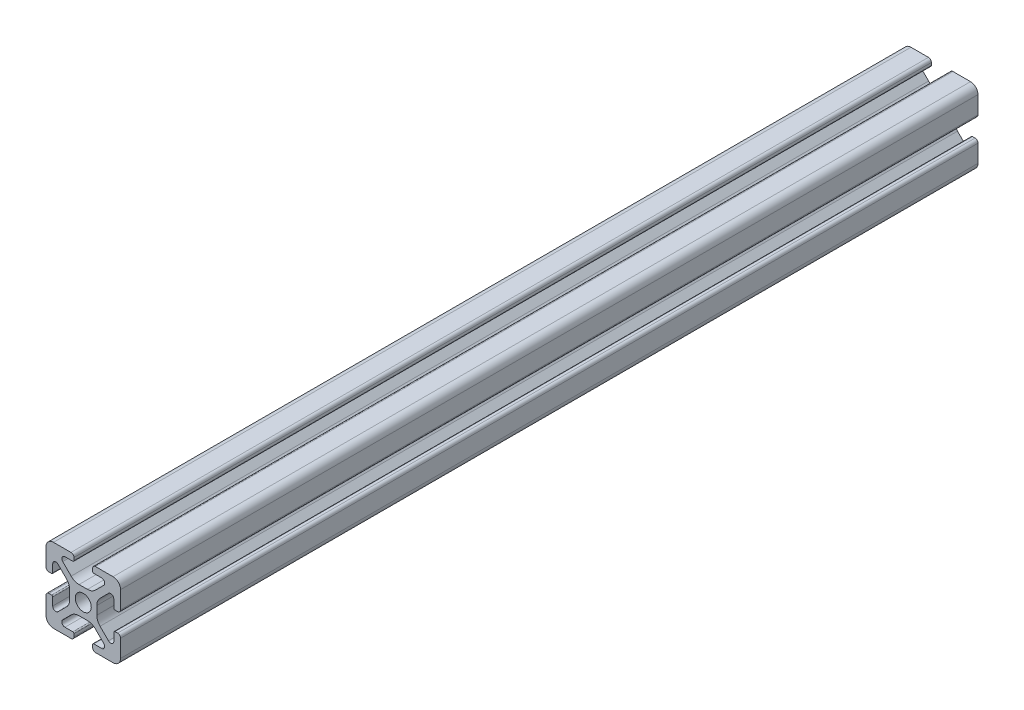
SolidWorks part; units mm, degrees
ref_plane "Front Plane" through (0, 0, 0) normal (0, 0, 1) x (1, 0, 0)
ref_plane "Top Plane" through (0, 0, 0) normal (0, 1, 0) x (1, 0, 0)
ref_plane "Right Plane" through (0, 0, 0) normal (1, 0, 0) x (0, 0, -1)
sketch "Sketch1" plane through (0, 0, 0) normal (0, 0, 1) x (1, 0, 0)
  line L2 (-9.9949, 7.9883) -> (-9.9949, 3.2893)
  line L3 (-7.9883, 9.9949) -> (-3.2893, 9.9949)
  line L4 (-2.5019, 9.2075) -> (-2.5019, 8.4963)
  line L5 (-2.8067, 8.1915) -> (-4.9149, 8.1915)
  line L6 (-5.5076, 6.7606) -> (-3.2528, 4.5058)
  line L7 (-6.7606, 5.5076) -> (-4.5058, 3.2528)
  line L8 (-8.1915, 4.9149) -> (-8.1915, 2.8067)
  line L9 (-8.4963, 2.5019) -> (-9.2075, 2.5019)
  line L11 (-1.1334, 3.6279) -> (1.1334, 3.6279)
  line L12 (-3.6279, 1.1334) -> (-3.6279, -1.1334)
  line L13 (8.4963, 2.5019) -> (9.2075, 2.5019)
  line L14 (8.1915, 4.9149) -> (8.1915, 2.8067)
  line L15 (9.9949, 7.9883) -> (9.9949, 3.2893)
  line L16 (7.9883, 9.9949) -> (3.2893, 9.9949)
  line L17 (2.5019, 9.2075) -> (2.5019, 8.4963)
  line L18 (2.8067, 8.1915) -> (4.9149, 8.1915)
  line L19 (3.6279, 1.1334) -> (3.6279, -1.1334)
  line L20 (5.5076, 6.7606) -> (3.2528, 4.5058)
  line L21 (6.7606, 5.5076) -> (4.5058, 3.2528)
  line L22 (-8.4963, -2.5019) -> (-9.2075, -2.5019)
  line L23 (-8.1915, -4.9149) -> (-8.1915, -2.8067)
  line L24 (-6.7606, -5.5076) -> (-4.5058, -3.2528)
  line L25 (-5.5076, -6.7606) -> (-3.2528, -4.5058)
  line L26 (-2.8067, -8.1915) -> (-4.9149, -8.1915)
  line L27 (-2.5019, -9.2075) -> (-2.5019, -8.4963)
  line L28 (-7.9883, -9.9949) -> (-3.2893, -9.9949)
  line L29 (-9.9949, -7.9883) -> (-9.9949, -3.2893)
  line L30 (9.9949, -7.9883) -> (9.9949, -3.2893)
  line L31 (7.9883, -9.9949) -> (3.2893, -9.9949)
  line L32 (2.5019, -9.2075) -> (2.5019, -8.4963)
  line L33 (2.8067, -8.1915) -> (4.9149, -8.1915)
  line L34 (5.5076, -6.7606) -> (3.2528, -4.5058)
  line L35 (6.7606, -5.5076) -> (4.5058, -3.2528)
  line L36 (8.1915, -4.9149) -> (8.1915, -2.8067)
  line L37 (8.4963, -2.5019) -> (9.2075, -2.5019)
  line L38 (-1.1334, -3.6279) -> (1.1334, -3.6279)
  circle A0 centre (0, 0) radius 2.1463
  arc A1 (-9.9949, 7.9883) -> (-7.9883, 9.9949) centre (-7.9883, 7.9883) cw
  arc A2 (-6.7606, 5.5076) -> (-8.1915, 4.9149) centre (-7.3533, 4.9149) ccw
  arc A3 (-4.9149, 8.1915) -> (-5.5076, 6.7606) centre (-4.9149, 7.3533) ccw
  arc A4 (-3.2893, 9.9949) -> (-2.5019, 9.2075) centre (-3.2893, 9.2075) cw
  arc A5 (-9.9949, 3.2893) -> (-9.2075, 2.5019) centre (-9.2075, 3.2893) ccw
  arc A6 (-8.1915, 2.8067) -> (-8.4963, 2.5019) centre (-8.4963, 2.8067) cw
  arc A7 (-2.5019, 8.4963) -> (-2.8067, 8.1915) centre (-2.8067, 8.4963) cw
  arc A8 (-1.1334, 3.6279) -> (-3.2528, 4.5058) centre (-1.1334, 6.6251) cw
  arc A9 (-3.6279, 1.1334) -> (-4.5058, 3.2528) centre (-6.6251, 1.1334) ccw
  arc A10 (8.1915, 2.8067) -> (8.4963, 2.5019) centre (8.4963, 2.8067) ccw
  arc A11 (9.9949, 3.2893) -> (9.2075, 2.5019) centre (9.2075, 3.2893) cw
  arc A12 (9.9949, 7.9883) -> (7.9883, 9.9949) centre (7.9883, 7.9883) ccw
  arc A13 (3.2893, 9.9949) -> (2.5019, 9.2075) centre (3.2893, 9.2075) ccw
  arc A14 (2.5019, 8.4963) -> (2.8067, 8.1915) centre (2.8067, 8.4963) ccw
  arc A15 (1.1334, 3.6279) -> (3.2528, 4.5058) centre (1.1334, 6.6251) ccw
  arc A16 (3.6279, 1.1334) -> (4.5058, 3.2528) centre (6.6251, 1.1334) cw
  arc A17 (6.7606, 5.5076) -> (8.1915, 4.9149) centre (7.3533, 4.9149) cw
  arc A18 (4.9149, 8.1915) -> (5.5076, 6.7606) centre (4.9149, 7.3533) cw
  arc A19 (-3.6279, -1.1334) -> (-4.5058, -3.2528) centre (-6.6251, -1.1334) cw
  arc A20 (-1.1334, -3.6279) -> (-3.2528, -4.5058) centre (-1.1334, -6.6251) ccw
  arc A21 (-2.5019, -8.4963) -> (-2.8067, -8.1915) centre (-2.8067, -8.4963) ccw
  arc A22 (-8.1915, -2.8067) -> (-8.4963, -2.5019) centre (-8.4963, -2.8067) ccw
  arc A23 (-9.9949, -3.2893) -> (-9.2075, -2.5019) centre (-9.2075, -3.2893) cw
  arc A24 (-3.2893, -9.9949) -> (-2.5019, -9.2075) centre (-3.2893, -9.2075) ccw
  arc A25 (-4.9149, -8.1915) -> (-5.5076, -6.7606) centre (-4.9149, -7.3533) cw
  arc A26 (-6.7606, -5.5076) -> (-8.1915, -4.9149) centre (-7.3533, -4.9149) cw
  arc A27 (-9.9949, -7.9883) -> (-7.9883, -9.9949) centre (-7.9883, -7.9883) ccw
  arc A28 (9.9949, -7.9883) -> (7.9883, -9.9949) centre (7.9883, -7.9883) cw
  arc A29 (6.7606, -5.5076) -> (8.1915, -4.9149) centre (7.3533, -4.9149) ccw
  arc A30 (4.9149, -8.1915) -> (5.5076, -6.7606) centre (4.9149, -7.3533) ccw
  arc A31 (3.2893, -9.9949) -> (2.5019, -9.2075) centre (3.2893, -9.2075) cw
  arc A32 (9.9949, -3.2893) -> (9.2075, -2.5019) centre (9.2075, -3.2893) ccw
  arc A33 (8.1915, -2.8067) -> (8.4963, -2.5019) centre (8.4963, -2.8067) cw
  arc A34 (2.5019, -8.4963) -> (2.8067, -8.1915) centre (2.8067, -8.4963) cw
  arc A35 (1.1334, -3.6279) -> (3.2528, -4.5058) centre (1.1334, -6.6251) cw
  arc A36 (3.6279, -1.1334) -> (4.5058, -3.2528) centre (6.6251, -1.1334) ccw
extrude "Boss-Extrude1" add sketch "Sketch1" along normal mid plane 230
